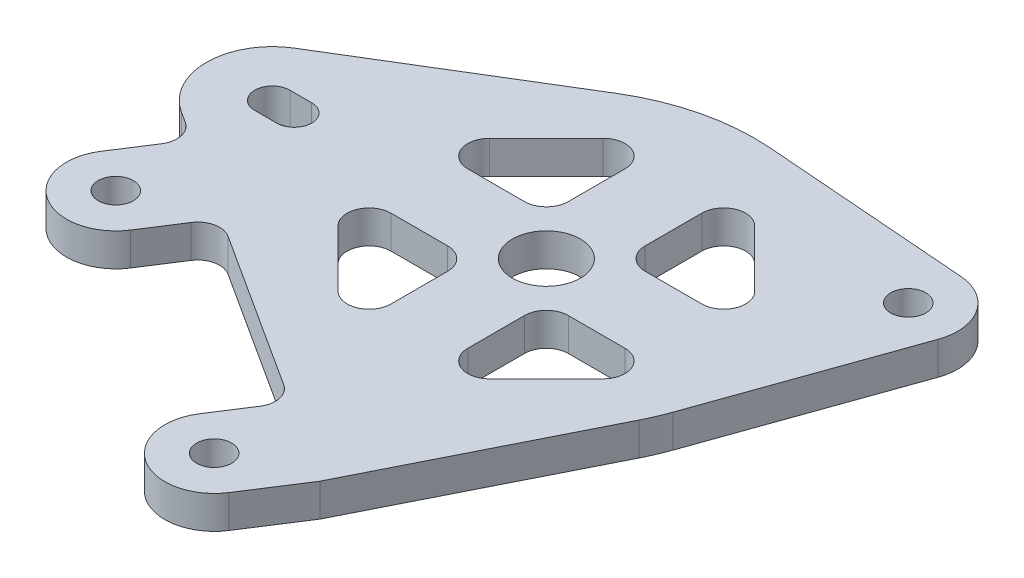
SolidWorks part; units mm, degrees
material "Thornel Mat VMA"
ref_plane "前视基准面" through (0, 0, 0) normal (0, 0, 1) x (1, 0, 0)
ref_plane "上视基准面" through (0, 0, 0) normal (0, 1, 0) x (1, 0, 0)
ref_plane "右视基准面" through (0, 0, 0) normal (1, 0, 0) x (0, 0, -1)
sketch "草图1" plane through (0, 0, 0) normal (0, 1, 0) x (1, 0, 0)
  line L0 (-60, 0) -> (-60, -7) construction
  line L1 (-60, -7) -> (-44.5, -7) construction
  line L2 (0, 0) -> (0, -7) construction
  line L3 (0, -7) -> (-15.5, -7) construction
  line L4 (-60, 0) -> (0, 0) construction
  line L5 (0, -7) -> (-7.75, 6.4234) construction
  line L6 (0, -7) -> (7.75, 6.4234) construction
  line L7 (0, -7) -> (15.5, -7) construction
  line L8 (0, -7) -> (7.75, -20.4234) construction
  line L9 (0, -7) -> (-7.75, -20.4234) construction
  line L10 (-60, -7) -> (-52.25, -20.4234) construction
  line L11 (-60, -7) -> (-67.75, -20.4234) construction
  line L12 (-60, -7) -> (-75.5, -7) construction
  line L13 (-60, -7) -> (-67.75, 6.4234) construction
  line L14 (-60, -7) -> (-52.25, 6.4234) construction
  line L15 (-100, 20) -> (-125, 20) construction
  line L16 (-100, 20) -> (-85, 20) construction
  line L17 (-100, 20) -> (-100, 1) construction
  line L18 (-96.5, 16.5) -> (-84.5, 16.5)
  line L19 (-125, 21.6) -> (-123, 21.6)
  line L20 (-125, 18.4) -> (-123, 18.4)
  line L21 (-30, 0) -> (-30, 39) construction
  line L22 (-100, 44.6) -> (-60, 44.6) construction
  line L23 (-100, 44.6) -> (-100, 20) construction
  line L24 (-60, 44.6) -> (-60, 0) construction
  line L25 (-60, -7) -> (-60, -30.1) construction
  line L26 (0, 0) -> (0, -7) construction
  line L27 (0, -7) -> (0, -30.1) construction
  line L28 (0, 44.6) -> (0, 0) construction
  line L29 (40, 44.6) -> (40, 20) construction
  line L30 (40, 44.6) -> (0, 44.6) construction
  line L31 (40, 20) -> (47.5, 32.9904) construction
  line L32 (40, 20) -> (47.5, 7.0096) construction
  line L33 (40, 20) -> (25, 20) construction
  line L34 (40, 20) -> (65, 20) construction
  line L35 (65, 18.4) -> (63, 18.4)
  line L36 (65, 21.6) -> (63, 21.6)
  line L37 (-100, 39) -> (40, 39)
  line L38 (-104.5, 44.6) -> (-104.5, 38.4594)
  line L39 (-95.5, 44.6) -> (-95.5, 39)
  line L40 (-64.5, 44.6) -> (-64.5, 39)
  line L41 (-55.5, 44.6) -> (-55.5, 39)
  line L42 (-4.5, 44.6) -> (-4.5, 39)
  line L43 (4.5, 44.6) -> (4.5, 39)
  line L44 (44.5, 44.6) -> (44.5, 38.4594)
  line L45 (35.5, 44.6) -> (35.5, 39)
  line L46 (-109.88, 36.2292) -> (-128.12, 25.125)
  line L47 (-128.2491, 14.9559) -> (-70.0181, -22.5528)
  line L48 (-64.5, -30.1) -> (-64.5, -24.9444)
  line L49 (-60, -25.5) -> (0, -25.5)
  line L50 (4.5, -30.1) -> (4.5, -24.9444)
  line L51 (-4.5, -30.1) -> (-4.5, -25.5)
  line L52 (-55.5, -30.1) -> (-55.5, -25.5)
  line L53 (49.88, 36.2292) -> (68.12, 25.125)
  line L54 (68.2491, 14.9559) -> (10.0181, -22.5528)
  line L55 (-67.9411, 35) -> (-34, 35)
  line L56 (-34, 35) -> (-34, 1.0589)
  line L57 (-34, 1.0589) -> (-67.9411, 35)
  line L58 (-73.598, 35) -> (-73.598, 10)
  line L59 (-73.598, 10) -> (-59.4558, 20.8579)
  line L60 (-59.4558, 20.8579) -> (-73.598, 35)
  line L64 (-73.598, 35) -> (-78.4868, 35) construction
  line L65 (31.6508, -3.8604) -> (21.5625, -10.3586)
  line L66 (21.5625, 3.8851) -> (31.6508, -3.8604)
  line L67 (21.5625, -10.3586) -> (21.5625, 3.8851)
  line L68 (13.598, 10) -> (-0.5442, 20.8579)
  line L69 (13.598, 35) -> (13.598, 10)
  line L70 (-0.5442, 20.8579) -> (13.598, 35)
  line L71 (-26, 35) -> (-26, 1.0589)
  line L72 (7.9411, 35) -> (-26, 35)
  line L73 (-26, 1.0589) -> (7.9411, 35)
  line L74 (-75.7592, 31.4949) -> (-82.0943, 13.6451)
  line L75 (-125, 20) -> (-125, 5.726) construction
  line L76 (-121.2169, 3.2892) -> (-117.9678, 8.3333)
  line L77 (-125.534, 13.207) -> (-128.7831, 8.1628)
  line L78 (-100.3133, -3.0385) -> (-103.5624, -8.0827)
  line L79 (-92.7471, -7.9122) -> (-95.9962, -12.9563)
  line L80 (-34, -6.9411) -> (-34, -21.5)
  line L81 (-34, -21.5) -> (-44, -21.5)
  line L82 (-44, -21.5) -> (-34, -6.9411)
  line L83 (-26, -21.5) -> (-16, -21.5)
  line L84 (-26, -6.9411) -> (-26, -21.5)
  line L85 (-16, -21.5) -> (-26, -6.9411)
  line L86 (32.7471, -7.9122) -> (35.9962, -12.9563)
  line L87 (40.3133, -3.0385) -> (43.5624, -8.0827)
  line L88 (61.2169, 3.2892) -> (57.9678, 8.3333)
  line L89 (65.534, 13.207) -> (68.7831, 8.1628)
  line L90 (-98.5384, 38.9437) -> (-79.6538, 37.4867)
  line L91 (-83.0177, 11.4794) -> (-92.7471, -7.9122)
  line L92 (-84.5, 16.5) -> (-96.5, 4.5)
  line L93 (-96.5, 4.5) -> (-96.5, 16.5)
  line L94 (-115.5, 16.5) -> (-103.5, 16.5)
  line L95 (-103.5, 16.5) -> (-103.5, 4.5)
  line L96 (-103.5, 4.5) -> (-115.5, 16.5)
  line L97 (-103.5, 35.5) -> (-103.5, 23.5)
  line L98 (-103.5, 23.5) -> (-115.5, 23.5)
  line L99 (-115.5, 23.5) -> (-103.5, 35.5)
  line L100 (-84.5, 23.5) -> (-96.5, 23.5)
  line L101 (-96.5, 23.5) -> (-96.5, 35.5)
  line L102 (-96.5, 35.5) -> (-84.5, 23.5)
  circle A0 centre (0, 0) radius 6
  circle A1 centre (-60, 0) radius 6
  circle A2 centre (-15.5, -7) radius 1.6
  circle A3 centre (-44.5, -7) radius 1.6
  circle A4 centre (-7.75, 6.4234) radius 1.6
  circle A5 centre (7.75, 6.4234) radius 1.6
  circle A6 centre (15.5, -7) radius 1.6
  circle A7 centre (7.75, -20.4234) radius 1.6
  circle A8 centre (-7.75, -20.4234) radius 1.6
  circle A9 centre (-52.25, -20.4234) radius 1.6
  circle A10 centre (-67.75, -20.4234) radius 1.6
  circle A11 centre (-75.5, -7) radius 1.6
  circle A12 centre (-67.75, 6.4234) radius 1.6
  circle A13 centre (-52.25, 6.4234) radius 1.6
  circle A14 centre (-60, -7) radius 18.5
  circle A15 centre (-100, 20) radius 3.1
  arc A16 (-125, 21.6) -> (-125, 18.4) centre (-125, 20) ccw
  circle A21 centre (-100, 20) radius 19
  arc A22 (-123, 18.4) -> (-123, 21.6) centre (-123, 20) ccw
  circle A23 centre (-125, 20) radius 6
  circle A24 centre (-100, 44.6) radius 1.6
  circle A25 centre (-60, 44.6) radius 1.6
  circle A26 centre (-60, -30.1) radius 1.6
  circle A27 centre (0, -30.1) radius 1.6
  circle A28 centre (0, -7) radius 18.5
  circle A29 centre (0, 44.6) radius 1.6
  circle A30 centre (40, 44.6) radius 1.6
  circle A31 centre (65, 20) radius 6
  arc A32 (63, 18.4) -> (63, 21.6) centre (63, 20) cw
  circle A33 centre (40, 20) radius 19
  circle A34 centre (47.5, 32.9904) radius 1.6
  circle A35 centre (47.5, 7.0096) radius 1.6
  circle A36 centre (25, 20) radius 1.6
  arc A37 (65, 21.6) -> (65, 18.4) centre (65, 20) cw
  circle A38 centre (40, 20) radius 3.1
  circle A39 centre (-100, 44.6) radius 4.5
  circle A40 centre (-60, 44.6) radius 4.5
  circle A41 centre (-60, -30.1) radius 4.5
  circle A42 centre (0, -30.1) radius 4.5
  circle A43 centre (40, 44.6) radius 4.5
  circle A44 centre (0, 44.6) radius 4.5
  circle A45 centre (-80, 33) radius 1.6
  circle A48 centre (-99.7793, -10.5195) radius 1.6
  circle A49 centre (-125, 5.726) radius 1.6
  circle A50 centre (-125, 5.726) radius 4.5
  circle A51 centre (-99.7793, -10.5195) radius 4.5
  circle A52 centre (39.7793, -10.5195) radius 1.6
  circle A53 centre (39.7793, -10.5195) radius 4.5
  circle A54 centre (65, 5.726) radius 1.6
  circle A55 centre (65, 5.726) radius 4.5
  circle A56 centre (20, 33) radius 1.6
  circle A57 centre (-100, 20) radius 10.2
  circle A58 centre (40, 20) radius 10.2
  circle A59 centre (-80, 33) radius 4.5
  point P23 (0, -7)
  point P34 (-60, -7)
  point P46 (-100, 20)
  point P162 (-119.5923, 5.8112)
  point P173 (59.5923, 5.8112)
  point P199 (-100, 20)
  dimension "D1" = 12
  dimension "D4" = 3.2
  dimension "D9" = 6.2
  dimension "D10" = 3.5
  dimension "D12" = 3.2
  dimension "D16" = 37
  dimension "D17" = 38
  dimension "D19" = 12
  dimension "D20" = 3.2
  dimension "D22" = 23.1
  dimension "D23" = 3.2
  dimension "D24" = 9
  dimension "D25" = 12
  dimension "D34" = 20
  dimension "D35" = 3.2
  dimension "D36" = 3.2
  dimension "D42" = 9
  dimension "D40" = 6
  dimension "D39" = 3.2
  dimension "D43" = 9
  dimension "D48" = 20.4
  dimension "D49" = 9
  dimension "D2" = 7
  dimension "D3" = 15.5
  dimension "D7" = 60
  dimension "D8" = 15
  dimension "D11" = 25
  dimension "D14" = 40
  dimension "D15" = 20
  dimension "D18" = 2
  dimension "D21" = 24.6
  dimension "D26" = 4
  dimension "D27" = 4
  dimension "D28" = 4
  dimension "D29" = 48
  dimension "D30" = 45
  dimension "D31" = 4
  dimension "D32" = 25
  dimension "D33" = 20
  dimension "D37" = 13
  dimension "D38" = 6
  dimension "D41" = 90
  dimension "D44" = 4
  dimension "D45" = 8
  dimension "D46" = 10
  dimension "D47" = 30
  dimension "D13" = 3.5
  dimension "D5" = 6
  dimension "D6" = 6
extrude "凸台-拉伸1" add sketch "草图1" along normal blind 3 contours L18 A57 L100 L101 L97 L98 L94 L95 L93 A15 | A21 A57 L18 L92 L93 L95 L96 L94 L98 L99 L97 L101 L102 L100 | A23 L47 L91 A21 | A23 A21 L46 | A59 L90 A21 L74 | A59 A45 | A23 A22 L20 A16 L19 | A50 L76 L47 L77 | A50 A49 | A51 L79 L47 L78 | A51 A48
fillet "圆角1" radius 2 15 edges at (-125.534, 1.5, -13.207) (-117.9678, 1.5, -8.3333) (-100.3133, 1.5, 3.0385) (-96.5, 1.5, -4.5) (-96.5, 1.5, -16.5) (-84.5, 1.5, -16.5) (-84.5, 1.5, -23.5) (-96.5, 1.5, -23.5) (-96.5, 1.5, -35.5) (-103.5, 1.5, -35.5) (-103.5, 1.5, -23.5) (-115.5, 1.5, -23.5) (-115.5, 1.5, -16.5) (-103.5, 1.5, -4.5) (-103.5, 1.5, -16.5)
equation "\"3。2\"=10"
